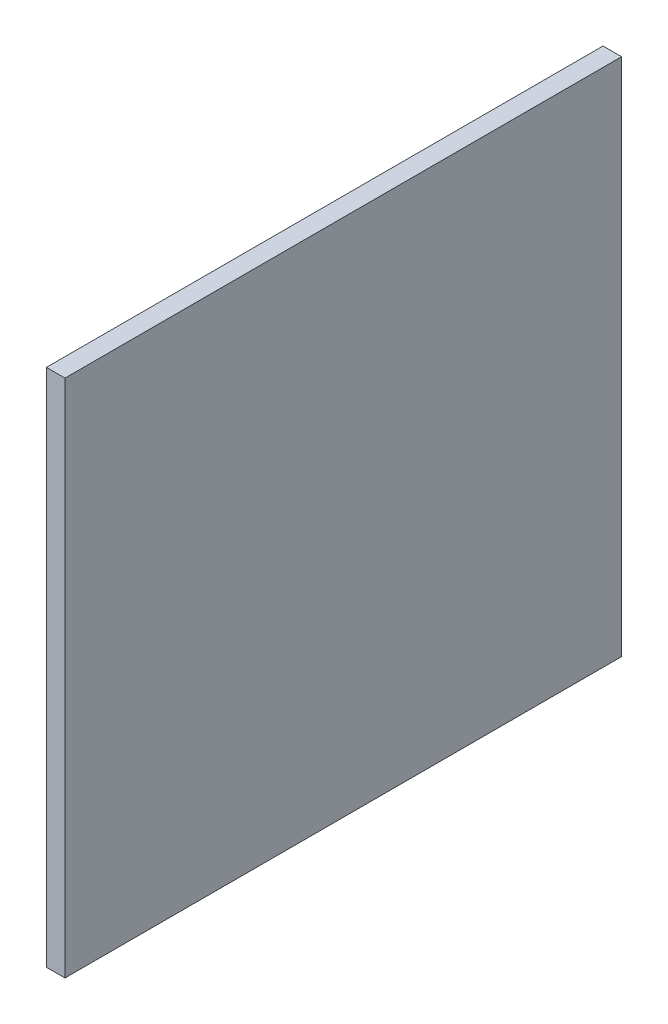
SolidWorks part; units mm, degrees
ref_plane "Front Plane" through (0, 0, 0) normal (0, 0, 1) x (1, 0, 0)
ref_plane "Top Plane" through (0, 0, 0) normal (0, 1, 0) x (1, 0, 0)
ref_plane "Right Plane" through (0, 0, 0) normal (1, 0, 0) x (0, 0, -1)
sketch "Sketch1" plane through (0, 0, 0) normal (1, 0, 0) x (0, 0, -1)
  line L1 (0, 0) -> (750, 0)
  line L2 (0, 0) -> (0, 700)
  line L3 (0, 700) -> (750, 700)
  line L4 (750, 0) -> (750, 700)
  dimension "D1" = 750
  dimension "D2" = 700
extrude "Boss-Extrude1" add sketch "Sketch1" along normal blind 25
